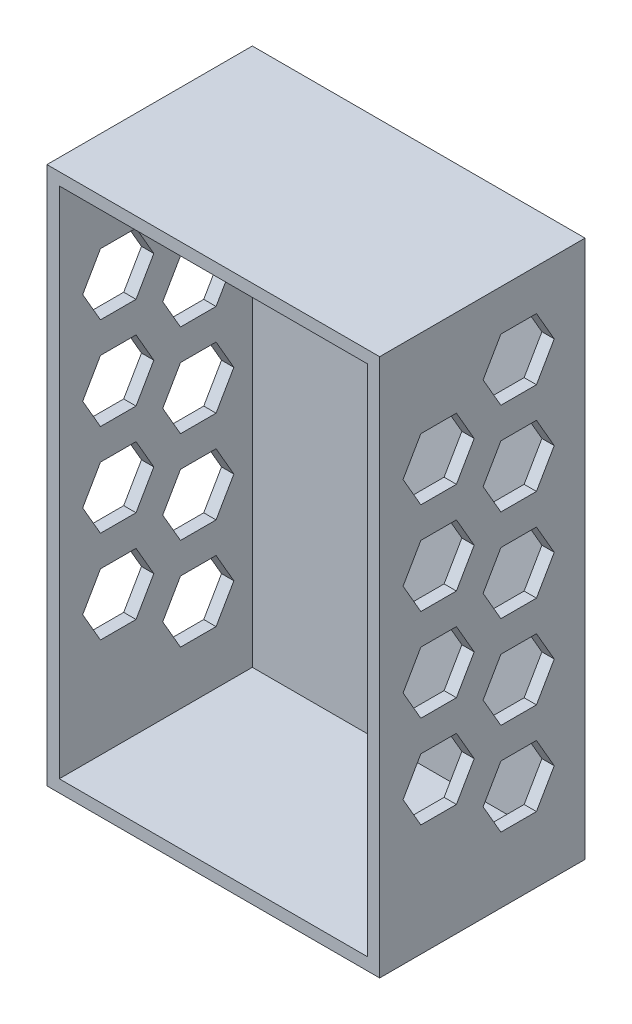
SolidWorks part; units mm, degrees
ref_plane "Front Plane" through (0, 0, 0) normal (0, 0, 1) x (1, 0, 0)
ref_plane "Top Plane" through (0, 0, 0) normal (0, 1, 0) x (1, 0, 0)
ref_plane "Right Plane" through (0, 0, 0) normal (1, 0, 0) x (0, 0, -1)
sketch "Sketch1" plane through (0, 0, 0) normal (0, 0, 1) x (1, 0, 0)
  line L1 (-16.2, 26.2) -> (16.2, 26.2)
  line L2 (-16.2, 26.2) -> (-16.2, -26.2)
  line L3 (-16.2, -26.2) -> (16.2, -26.2)
  line L4 (16.2, 26.2) -> (16.2, -26.2)
  line L5 (-16.2, 26.2) -> (16.2, -26.2) construction
  line L6 (-16.2, -26.2) -> (16.2, 26.2) construction
  point P0 (0, 0)
  dimension "D1" = 52.4
  dimension "D2" = 32.4
extrude "Boss-Extrude1" add sketch "Sketch1" along normal blind 20
shell "Shell1" thickness 1.2
sketch "Sketch2" plane through (16.2, 0, 0) normal (1, 0, 0) x (0, 0, -1)
  line L9 (-20, 26.2) -> (0, 26.2) construction
  line L10 (-3, 19.2) -> (-4.7321, 22.2)
  line L11 (-4.7321, 22.2) -> (-8.1962, 22.2)
  line L12 (-8.1962, 22.2) -> (-9.9282, 19.2)
  line L17 (-9.9282, 19.2) -> (-8.1962, 16.2)
  line L18 (-8.1962, 16.2) -> (-4.7321, 16.2)
  line L19 (-4.7321, 16.2) -> (-3, 19.2)
  line L20 (0, -26.2) -> (0, 26.2) construction
  line L21 (-6.4641, 19.2) -> (-14.2583, 14.7) construction
  line L22 (-3, 10.2) -> (-4.7321, 13.2)
  line L23 (-10.7942, 14.7) -> (-12.5263, 17.7)
  line L24 (-12.5263, 17.7) -> (-15.9904, 17.7)
  line L25 (-15.9904, 17.7) -> (-17.7224, 14.7)
  line L26 (-17.7224, 14.7) -> (-15.9904, 11.7)
  line L27 (-15.9904, 11.7) -> (-12.5263, 11.7)
  line L28 (-12.5263, 11.7) -> (-10.7942, 14.7)
  line L29 (-4.7321, 13.2) -> (-8.1962, 13.2)
  line L30 (-8.1962, 13.2) -> (-9.9282, 10.2)
  line L31 (-9.9282, 10.2) -> (-8.1962, 7.2)
  line L32 (-8.1962, 7.2) -> (-4.7321, 7.2)
  line L33 (-4.7321, 7.2) -> (-3, 10.2)
  line L34 (-3, 1.2) -> (-4.7321, 4.2)
  line L35 (-4.7321, 4.2) -> (-8.1962, 4.2)
  line L36 (-8.1962, 4.2) -> (-9.9282, 1.2)
  line L37 (-9.9282, 1.2) -> (-8.1962, -1.8)
  line L38 (-8.1962, -1.8) -> (-4.7321, -1.8)
  line L39 (-4.7321, -1.8) -> (-3, 1.2)
  line L40 (-3, -7.8) -> (-4.7321, -4.8)
  line L41 (-4.7321, -4.8) -> (-8.1962, -4.8)
  line L42 (-8.1962, -4.8) -> (-9.9282, -7.8)
  line L43 (-9.9282, -7.8) -> (-8.1962, -10.8)
  line L44 (-8.1962, -10.8) -> (-4.7321, -10.8)
  line L45 (-4.7321, -10.8) -> (-3, -7.8)
  line L46 (-3, -16.8) -> (-4.7321, -13.8)
  line L47 (-4.7321, -13.8) -> (-8.1962, -13.8)
  line L48 (-8.1962, -13.8) -> (-9.9282, -16.8)
  line L49 (-9.9282, -16.8) -> (-8.1962, -19.8)
  line L50 (-8.1962, -19.8) -> (-4.7321, -19.8)
  line L51 (-4.7321, -19.8) -> (-3, -16.8)
  line L52 (-10.7942, 5.7) -> (-12.5263, 8.7)
  line L53 (-12.5263, 8.7) -> (-15.9904, 8.7)
  line L54 (-15.9904, 8.7) -> (-17.7224, 5.7)
  line L55 (-17.7224, 5.7) -> (-15.9904, 2.7)
  line L56 (-15.9904, 2.7) -> (-12.5263, 2.7)
  line L57 (-12.5263, 2.7) -> (-10.7942, 5.7)
  line L58 (-10.7942, -3.3) -> (-12.5263, -0.3)
  line L59 (-12.5263, -0.3) -> (-15.9904, -0.3)
  line L60 (-15.9904, -0.3) -> (-17.7224, -3.3)
  line L61 (-17.7224, -3.3) -> (-15.9904, -6.3)
  line L62 (-15.9904, -6.3) -> (-12.5263, -6.3)
  line L63 (-12.5263, -6.3) -> (-10.7942, -3.3)
  line L64 (-10.7942, -12.3) -> (-12.5263, -9.3)
  line L65 (-12.5263, -9.3) -> (-15.9904, -9.3)
  line L66 (-15.9904, -9.3) -> (-17.7224, -12.3)
  line L67 (-17.7224, -12.3) -> (-15.9904, -15.3)
  line L68 (-15.9904, -15.3) -> (-12.5263, -15.3)
  line L69 (-12.5263, -15.3) -> (-10.7942, -12.3)
  circle A0 centre (-6.4641, 19.2) radius 3 construction
  circle A1 centre (-14.2583, 14.7) radius 3 construction
  circle A2 centre (-6.4641, 10.2) radius 3 construction
  circle A3 centre (-6.4641, 1.2) radius 3 construction
  circle A4 centre (-6.4641, -7.8) radius 3 construction
  circle A5 centre (-6.4641, -16.8) radius 3 construction
  circle A6 centre (-14.2583, 5.7) radius 3 construction
  circle A7 centre (-14.2583, -3.3) radius 3 construction
  circle A8 centre (-14.2583, -12.3) radius 3 construction
  dimension "D1" = 6
  dimension "D2" = 4
  dimension "D3" = 3
  dimension "D4" = 9
  dimension "D5" = 5
  dimension "D6" = 4
extrude "Cut-Extrude1" cut sketch "Sketch2" against normal through all
